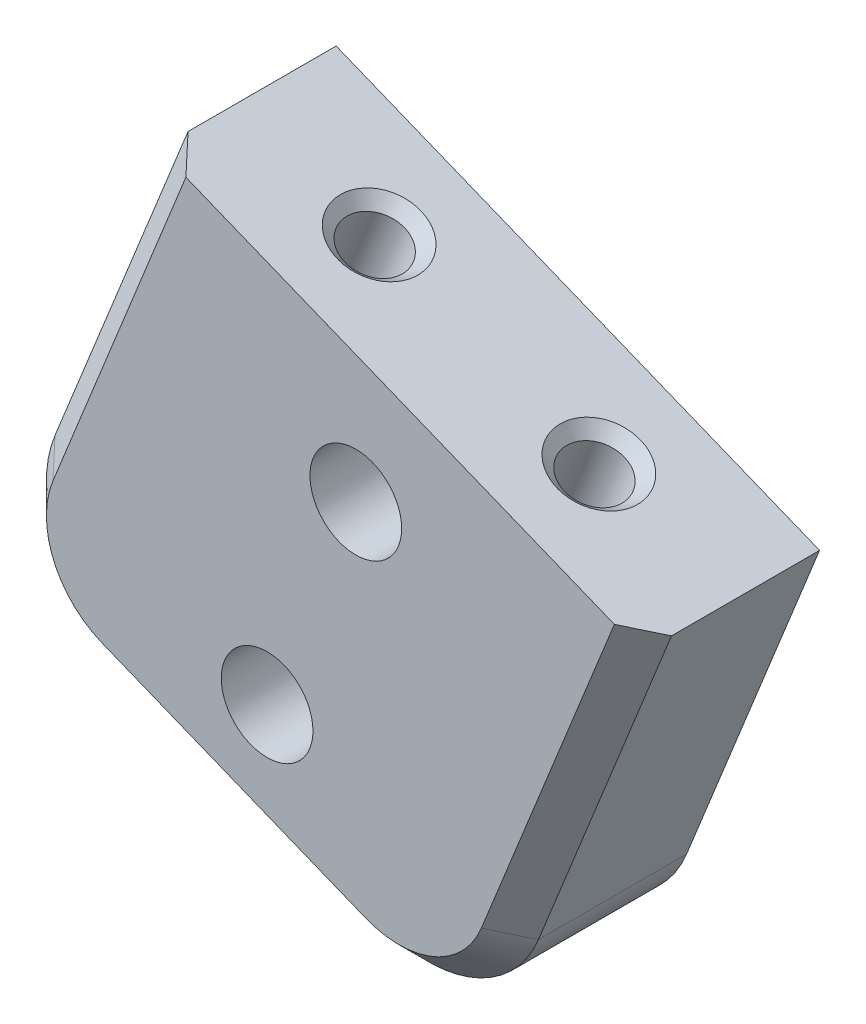
SolidWorks part; units mm, degrees
material "PET"
ref_plane "Front Plane" through (0, 0, 0) normal (0, 0, 1) x (1, 0, 0)
ref_plane "Top Plane" through (0, 0, 0) normal (0, 1, 0) x (1, 0, 0)
ref_plane "Right Plane" through (0, 0, 0) normal (1, 0, 0) x (0, 0, -1)
sketch "Sketch1" plane through (0, 0, 0) normal (0, 0, 1) x (1, 0, 0)
  line L0 (822.9635, 732.8636) -> (813.4572, 709.3096)
  line L1 (822.9635, 732.8636) -> (797.0541, 743.3205)
  line L2 (813.4572, 709.3096) -> (787.5478, 719.7665)
  line L3 (797.0541, 743.3205) -> (787.5478, 719.7665)
  line L4 (797.0541, 743.3205) -> (822.9635, 732.8636) construction
  line L6 (822.9635, 732.8636) -> (832.4697, 756.4176) construction
  line L7 (806.5603, 766.8745) -> (797.0541, 743.3205) construction
  dimension "D2" = 25.4
extrude "Boss-Extrude1" add sketch "Sketch1" along normal blind 9.525
fillet "Fillet1" radius 6.35 2 edges at (787.5478, 719.7665, 4.7625) (813.4572, 709.3096, 4.7625)
chamfer "Chamfer3" distance 1.5875 angle 45 5 edges at (793.4892, 734.4878, 9.525) (789.9686, 720.7951, 9.525) (800.5025, 714.5381, 9.525) (812.4286, 711.7304, 9.525) (819.3986, 724.0309, 9.525)
hole_wizard "1/8 (0.126) Dowel Hole1" positions "Sketch2" profile "Sketch3" hole size "1/8" standard "ANSI Inch"
sketch "Sketch2" plane through (369.6233, 915.8291, 0) normal (0.3743, 0.9273, 0) x (0.9273, -0.3743, 0)
  line L0 (474.8998, 0) -> (474.8998, -9.525) construction
  line L1 (488.8698, 0) -> (460.9298, 0) construction
  line L2 (487.2823, -9.525) -> (462.5173, -9.525) construction
  point P8 (468.5498, -4.7625)
  point P11 (474.8998, -4.7625)
  point P12 (0, 0)
  point P13 (481.2498, -4.7625)
  dimension "D1" = 6.35
sketch "Sketch3" plane through (815.8973, 735.7155, 4.7625) normal (0, 0, 1) x (-0.9273, 0.3743, 0)
  line L0 (0, 0) -> (0, 12.074)
  line L1 (0, 12.074) -> (1.6002, 11.1125)
  line L2 (1.6002, 11.1125) -> (1.6002, 0.635)
  line L3 (1.6002, 0.635) -> (2.2352, 0)
  line L5 (2.2352, 0) -> (0, 0)
  line L6 (-1.6002, 0.635) -> (-2.2352, 0) construction
  line L10 (0, 12.074) -> (-1.6002, 11.1125) construction
  line L11 (0, -6.35) -> (0, 107.95) construction
  dimension "Hole Dia." = 3.2004
  dimension "Hole Depth" = 11.1125
  dimension "Near C'Sink Dia." = 4.4704
  dimension "Near C'Sink Angle" = 90
  dimension "Drill Angle" = 118
hole_wizard "1/16 (0.0625) Diameter Hole1" positions "Sketch4" profile "Sketch5" hole size "1/16" standard "ANSI Inch" end condition through all
sketch "Sketch4" plane through (369.6233, 915.8291, 0) normal (0.3743, 0.9273, 0) x (0.9273, -0.3743, 0)
  point P0 (468.5498, -4.7625)
  point P3 (481.2498, -4.7625)
sketch "Sketch5" plane through (804.1203, 740.4687, 4.7625) normal (0, 0, 1) x (-0.9273, 0.3743, 0)
  line L0 (0, 0) -> (0, 32.6043)
  line L1 (0, 32.6043) -> (0.7937, 32.6043)
  line L2 (0.7937, 32.6043) -> (0.7937, 0)
  line L5 (0.7937, 0) -> (0, 0)
  line L11 (0, -6.35) -> (0, 107.95) construction
  dimension "Thru Hole Dia." = 1.5875
  dimension "Thru Hole Depth" = 32.6043
hole_wizard "#8 Clearance Hole1" positions "Sketch8" profile "Sketch9" hole size "#8" standard "ANSI Inch" end condition through all
sketch "Sketch8" plane through (0, 0, 9.525) normal (0, 0, 1) x (1, 0, 0)
  line L0 (800.5025, 714.5381) -> (810.0088, 738.0921) construction
  line L1 (807.5687, 711.6862) -> (793.4363, 717.39) construction
  line L2 (821.4913, 733.4578) -> (798.5262, 742.7264) construction
  point P9 (807.6322, 732.2036)
  point P11 (802.8791, 720.4266)
  dimension "D1" = 6.35
  dimension "D2" = 6.35
sketch "Sketch9" plane through (802.8791, 720.4266, 9.525) normal (1, 0, 0) x (0, -1, 0)
  line L0 (0, 0) -> (0, 9.525)
  line L1 (0, 9.525) -> (2.4574, 9.525)
  line L2 (2.4574, 9.525) -> (2.4574, 0)
  line L5 (2.4574, 0) -> (0, 0)
  line L11 (0, -6.35) -> (0, 107.95) construction
  dimension "Thru Hole Dia." = 4.9149
  dimension "Thru Hole Depth" = 9.525
